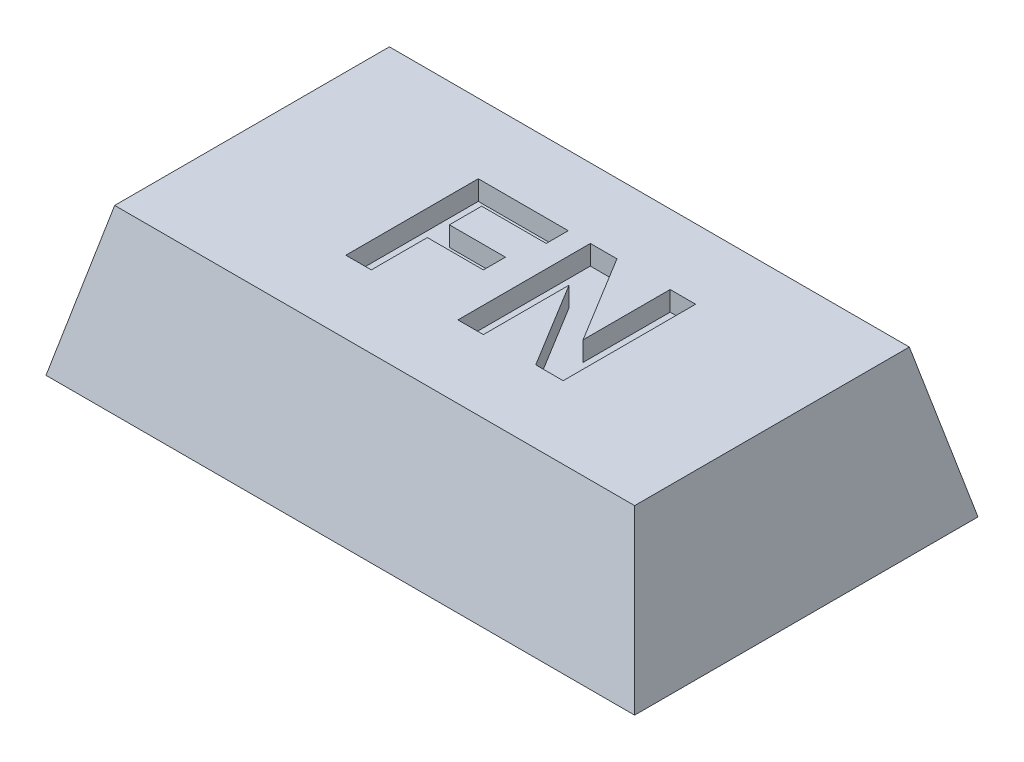
SolidWorks part; units mm, degrees
ref_plane "Front Plane" through (0, 0, 0) normal (0, 0, 1) x (1, 0, 0)
ref_plane "Top Plane" through (0, 0, 0) normal (0, 1, 0) x (1, 0, 0)
ref_plane "Right Plane" through (0, 0, 0) normal (1, 0, 0) x (0, 0, -1)
sketch "Sketch1" plane through (0, 0, 0) normal (0, 1, 0) x (1, 0, 0)
  line L1 (0, 0) -> (12, 0)
  line L2 (0, 0) -> (0, 7)
  line L3 (0, 7) -> (12, 7)
  line L4 (12, 0) -> (12, 7)
  dimension "D1" = 7
  dimension "D2" = 12
extrude "Boss-Extrude1" add sketch "Sketch1" along normal blind 3
sketch "Sketch2" plane through (0, 0, 0) normal (0, 0, 1) x (1, 0, 0)
  line L0 (0, 0) -> (0.7, 3)
  line L1 (0, 3) -> (12, 3) construction
  line L2 (0.7, 3) -> (0, 3)
  line L3 (0, 3) -> (0, 0)
  line L4 (12, 0) -> (11.3, 3)
  line L5 (11.3, 3) -> (12, 3)
  line L6 (12, 3) -> (12, 0)
  dimension "D1" = 0.7
  dimension "D2" = 0.7
extrude "Cut-Extrude1" cut sketch "Sketch2" against normal blind 7
sketch "Sketch3" plane through (0, 0, 0) normal (1, 0, 0) x (0, 0, -1)
  line L0 (0, 0) -> (0.7, 3)
  line L1 (7, 3) -> (0, 3) construction
  line L2 (0.7, 3) -> (0, 3)
  line L3 (0, 3) -> (0, 0)
  line L4 (7, 3) -> (6.3, 3)
  line L5 (6.3, 3) -> (7, 0)
  line L6 (7, 3) -> (7, 0)
  dimension "D1" = 0.7
  dimension "D2" = 0.7
extrude "Cut-Extrude2" cut sketch "Sketch3" along normal through all both and the other way through all
sketch "Sketch4" plane through (0, 0, 0) normal (0, -1, 0) x (1, 0, 0)
  line L0 (6, 0) -> (6, -7) construction
  line L1 (0, 0) -> (12, 0) construction
  line L2 (12, -7) -> (0, -7) construction
  line L3 (0, -3.5) -> (12, -3.5) construction
  line L4 (0, -7) -> (0, 0) construction
  line L5 (12, 0) -> (12, -7) construction
  circle A0 centre (6, -3.5) radius 1.8
  dimension "D1" = 3.6
extrude "Cut-Extrude3" cut sketch "Sketch4" against normal blind 0.8
sketch "Sketch5" plane through (0, 3, 0) normal (0, 1, 0) x (1, 0, 0)
  text T0 "FN" font "Arial" height 2.7
extrude "Cut-Extrude4" cut sketch "Sketch5" against normal blind 0.4
